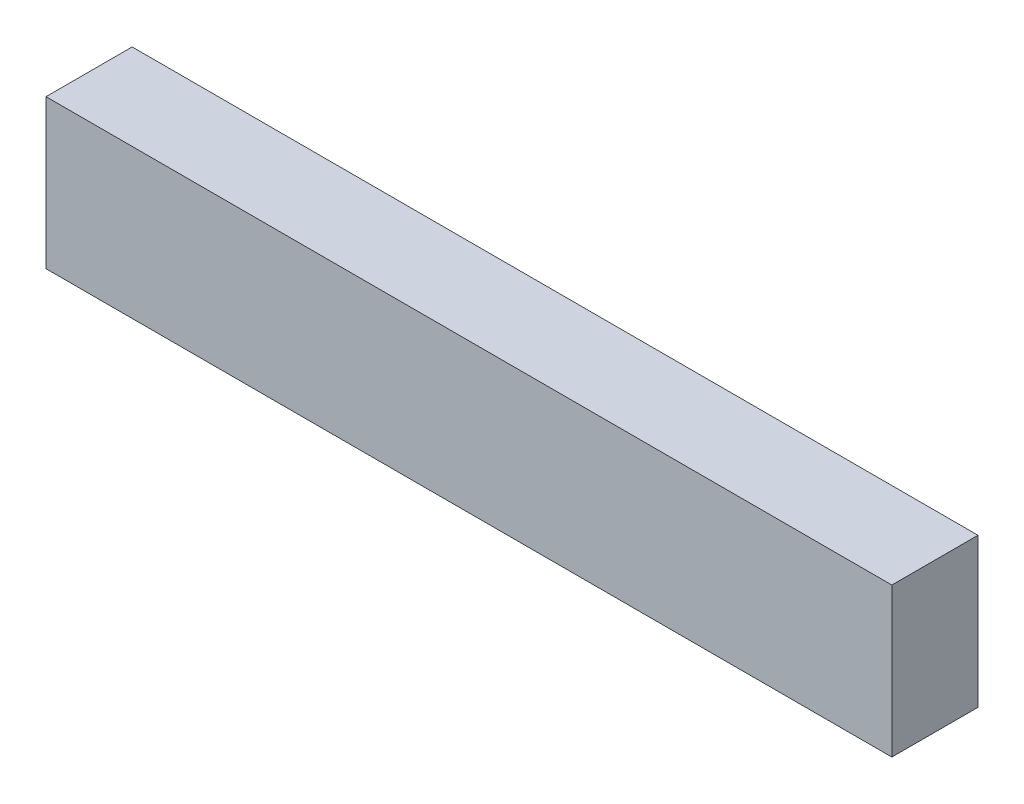
SolidWorks part; units mm, degrees
ref_plane "Front Plane" through (0, 0, 0) normal (0, 0, 1) x (1, 0, 0)
ref_plane "Top Plane" through (0, 0, 0) normal (0, 1, 0) x (1, 0, 0)
ref_plane "Right Plane" through (0, 0, 0) normal (1, 0, 0) x (0, 0, -1)
sketch "Sketch1" plane through (0, 0, 0) normal (0, 0, 1) x (1, 0, 0)
  line L0 (-79.2368, -1.49) -> (-7.6555, -1.49) construction
  line L1 (-79.0368, -1.69) -> (-7.8555, -1.69)
  line L2 (-79.0368, -1.69) -> (-79.0368, -14.23)
  line L3 (-79.0368, -14.23) -> (-7.8555, -14.23)
  line L4 (-7.8555, -1.69) -> (-7.8555, -14.23)
  line L5 (-7.6555, -1.49) -> (-7.6555, -14.43) construction
  line L6 (-7.6555, -14.43) -> (-79.2368, -14.43) construction
  line L7 (-79.2368, -1.49) -> (-79.2368, -14.43) construction
  dimension "D1" = 0.2
  dimension "D2" = 0.2
  dimension "D3" = 0.2
  dimension "D4" = 0.2
extrude "Boss-Extrude1" add sketch "Sketch1" along normal blind 7.25
shell "Shell1" thickness 0.5
equation "\"D2@Sketch1\"=\"D1@Sketch1\""
equation "\"D3@Sketch1\"=\"D1@Sketch1\""
equation "\"D4@Sketch1\"=\"D1@Sketch1\""
